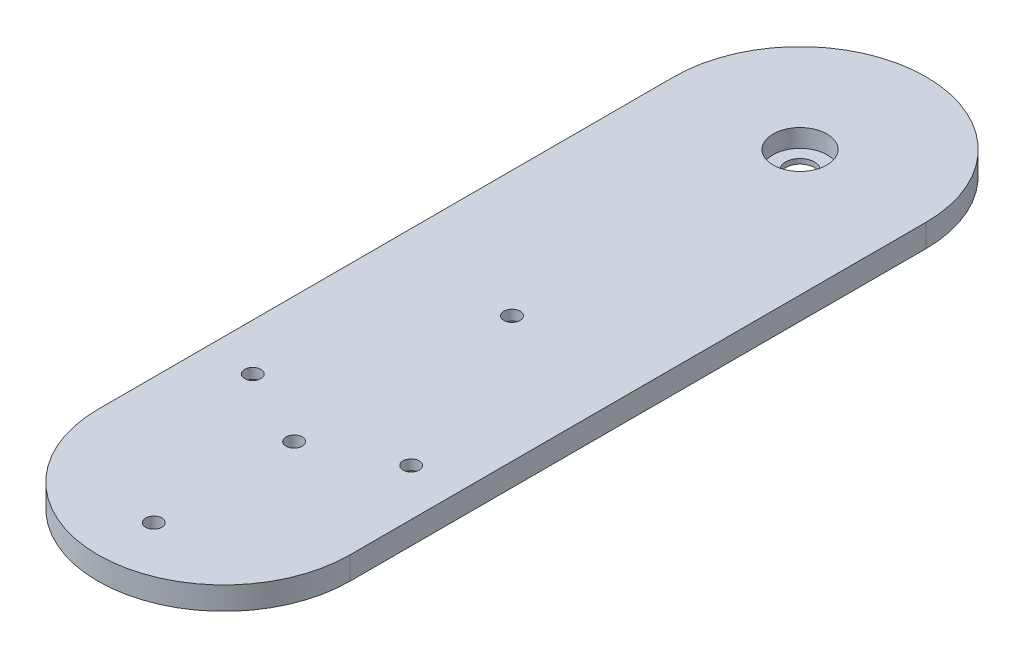
SolidWorks part; units mm, degrees
material "Aleación 6061"
ref_plane "Alzado" through (0, 0, 0) normal (0, 0, 1) x (1, 0, 0)
ref_plane "Planta" through (0, 0, 0) normal (0, 1, 0) x (1, 0, 0)
ref_plane "Vista lateral" through (0, 0, 0) normal (1, 0, 0) x (0, 0, -1)
sketch "Sk_Placa" plane through (0, 0, 0) normal (0, 1, 0) x (1, 0, 0)
  line L1 (-35, -330) -> (35, -330)
  line L2 (-35, -330) -> (-35, -170)
  line L3 (-35, -170) -> (35, -170)
  line L4 (35, -330) -> (35, -170)
  line L5 (-35, -330) -> (35, -170) construction
  line L6 (-35, -170) -> (35, -330) construction
  point P0 (0, -250)
  dimension "D1" = 70
  dimension "D2" = 160
  dimension "D3" = 250
extrude "Placa" add sketch "Sk_Placa" along normal blind 6.35 from offset 53.1
sketch "Sk_Extremos" plane through (0, 0, 0) normal (0, 1, 0) x (1, 0, 0)
  circle A0 centre (0, -170) radius 35
  circle A1 centre (0, -330) radius 35
  dimension "D1" = 70
  dimension "D3" = 70
  dimension "D2" = 170
  dimension "D4" = 330
extrude "Extremos" add sketch "Sk_Extremos" along normal blind 6.35 from offset 53.1
sketch "Sk_Pasantes_M4_separadores" plane through (0, 0, 0) normal (0, 1, 0) x (1, 0, 0)
  circle A0 centre (0, -250) radius 2.25
  circle A1 centre (-22, -300) radius 2.25
  circle A2 centre (22, -300) radius 2.25
  dimension "D1" = 4.5
  dimension "D3" = 4.5
  dimension "D6" = 4.5
  dimension "D2" = 250
  dimension "D4" = 22
  dimension "D5" = 300
  dimension "D7" = 22
  dimension "D8" = 300
extrude "Pasantes_M4_separadores" cut sketch "Sk_Pasantes_M4_separadores" along normal blind 6.35 from offset 53.1
sketch "Sk_Alojamiento_696ZZ" plane through (0, 0, 0) normal (0, 1, 0) x (1, 0, 0)
  circle A0 centre (0, -170) radius 7.475
  dimension "D1" = 14.95
  dimension "D2" = 170
extrude "Alojamiento_696ZZ" cut sketch "Sk_Alojamiento_696ZZ" along normal blind 5 from offset 51.75
sketch "Sk_Paso_extractor" plane through (0, 0, 0) normal (0, 1, 0) x (1, 0, 0)
  circle A0 centre (0, -170) radius 4
  dimension "D1" = 8
  dimension "D2" = 170
extrude "Paso_extractor" cut sketch "Sk_Paso_extractor" along normal blind 1.35 from offset 53.1
sketch "Sk_Pasantes_M4_ejefalso_J3" plane through (0, 0, 0) normal (0, 1, 0) x (1, 0, 0)
  circle A0 centre (0, -310.5) radius 2.25
  circle A1 centre (0, -349.5) radius 2.25
  dimension "D1" = 4.5
  dimension "D3" = 4.5
  dimension "D2" = 310.5
  dimension "D4" = 349.5
extrude "Pasantes_M4_ejefalso_J3" cut sketch "Sk_Pasantes_M4_ejefalso_J3" along normal blind 6.35 from offset 53.1
sketch "Sk_Cajas_M4_separadores" plane through (0, -53.1, 0) normal (0, -1, 0) x (1, 0, 0)
  circle A0 centre (0, 250) radius 4
  circle A1 centre (22, 300) radius 4
  circle A2 centre (-22, 300) radius 4
extrude "Cajas_M4_separadores" cut sketch "Sk_Cajas_M4_separadores" against normal blind 3.5
